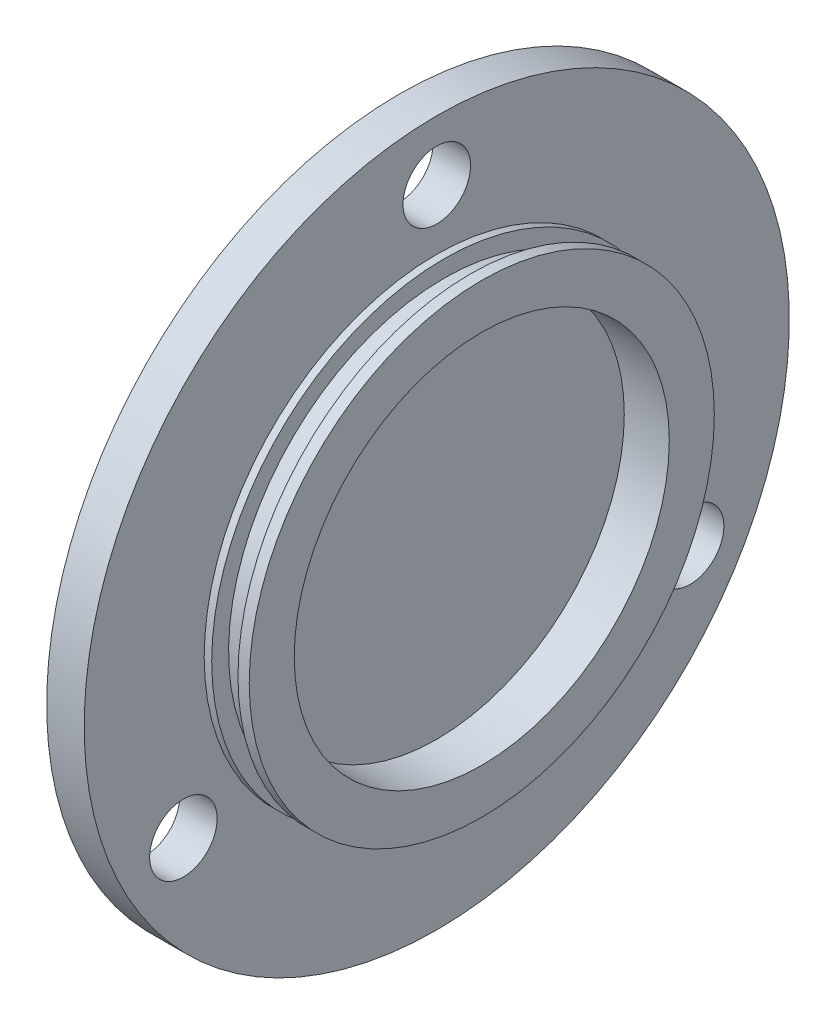
SolidWorks part; units mm, degrees
ref_plane "Piano frontale" through (0, 0, 0) normal (0, 0, 1) x (1, 0, 0)
ref_plane "Piano superiore" through (0, 0, 0) normal (0, 1, 0) x (1, 0, 0)
ref_plane "Piano destro" through (0, 0, 0) normal (1, 0, 0) x (0, 0, -1)
sketch "Schizzo1" plane through (0, 0, 0) normal (0, 0, 1) x (1, 0, 0)
  line L0 (0, 0) -> (0, 47)
  line L1 (0, 47) -> (5, 47)
  line L2 (5, 47) -> (5, 31)
  line L3 (5, 31) -> (6, 31)
  line L4 (11, 31) -> (11, 25)
  line L5 (11, 25) -> (5, 25)
  line L6 (5, 25) -> (5, 0)
  line L7 (5, 0) -> (0, 0)
  line L8 (6, 31) -> (6, 28.75)
  line L9 (6, 28.75) -> (9.5, 28.75)
  line L10 (9.5, 28.75) -> (9.5, 31)
  line L11 (9.5, 31) -> (11, 31)
  point P5 (11, 28)
  point P11 (2.5, 0)
  dimension "D1" = 5
  dimension "D2" = 31
  dimension "11" = 11
  dimension "D3" = 47
  dimension "D4" = 5
  dimension "D5" = 25
  dimension "D6" = 28.75
  dimension "D7" = 3.5
  dimension "1.5" = 1.5
revolve "Rivoluzione1" add sketch "Schizzo1" angle 360 about L7
sketch "Schizzo2" plane through (5, 0, 0) normal (1, 0, 0) x (0, 0, -1)
  circle A0 centre (0, 39) radius 4.5
  circle A1 centre (0, 0) radius 31 construction
  circle A2 centre (33.775, -19.5) radius 4.5
  circle A3 centre (-33.775, -19.5) radius 4.5
  point P11 (0, 0)
  dimension "D1" = 9
  dimension "D2" = 39
  dimension "D3" = 3
extrude "Taglio-Estrusione1" cut sketch "Schizzo2" against normal through all
